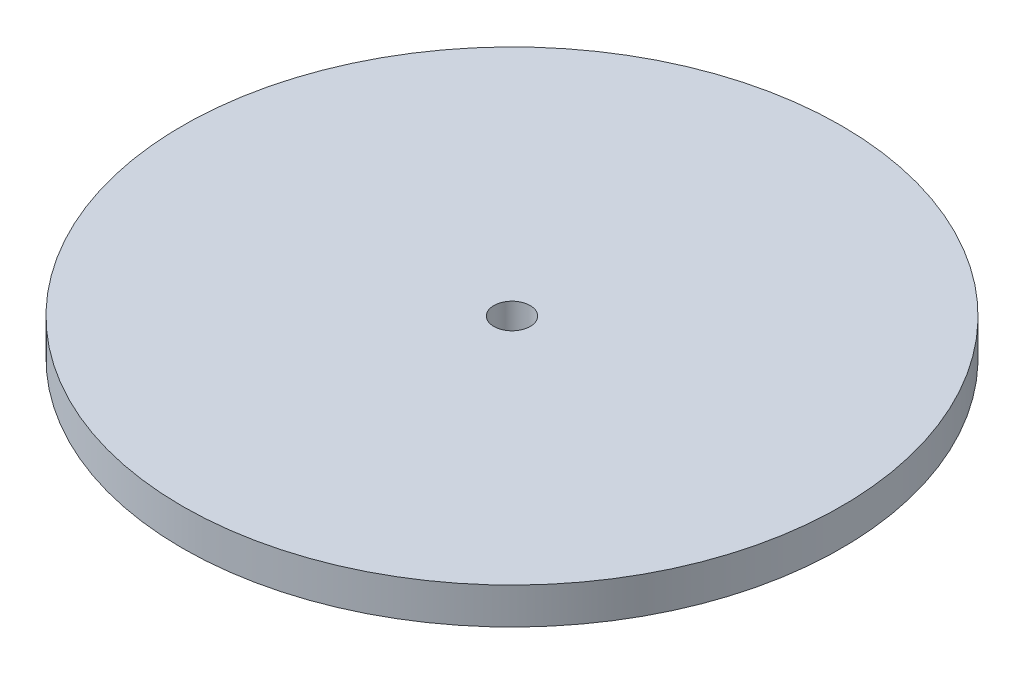
SolidWorks part; units mm, degrees
ref_plane "Front Plane" through (0, 0, 0) normal (0, 0, 1) x (1, 0, 0)
ref_plane "Top Plane" through (0, 0, 0) normal (0, 1, 0) x (1, 0, 0)
ref_plane "Right Plane" through (0, 0, 0) normal (1, 0, 0) x (0, 0, -1)
sketch "Sketch1" plane through (0, 0, 0) normal (0, 1, 0) x (1, 0, 0)
  circle A0 centre (0, 0) radius 36.25
  circle A1 centre (0, 0) radius 2
  dimension "D1" = 72.5
  dimension "D2" = 4
extrude "Boss-Extrude1" add sketch "Sketch1" along normal blind 4
